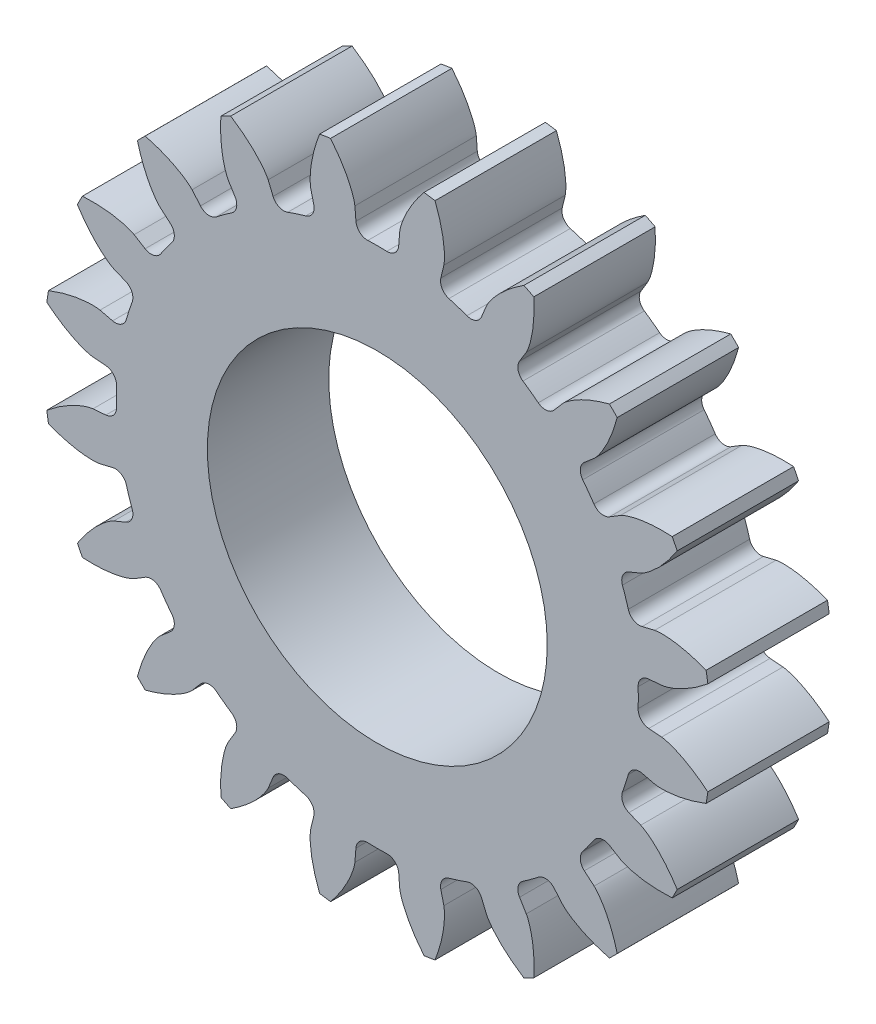
SolidWorks part; units mm, degrees
ref_plane "Front Plane" through (0, 0, 0) normal (0, 0, 1) x (1, 0, 0)
ref_plane "Top Plane" through (0, 0, 0) normal (0, 1, 0) x (1, 0, 0)
ref_plane "Right Plane" through (0, 0, 0) normal (1, 0, 0) x (0, 0, -1)
ref_axis "Gear Axis" through (0, 0, -0.2501) along (0, 0, 1)
sketch "Blank Sketch" plane through (0, 0, 0) normal (0, 0, 1) x (1, 0, 0)
  circle A0 centre (0, 0) radius 13.75
  dimension "OD" = 27.5
extrude "Blank" add sketch "Blank Sketch" along normal blind 5
sketch "Tooth Space Sketch" plane through (0, 0, 0) normal (0, 0, 1) x (1, 0, 0)
  line L0 (11.7099, 0.9227) -> (11.1803, 0.881)
  line L1 (11.7099, -0.9227) -> (11.1803, -0.881)
  line L2 (14.6961, 3.0042) -> (14.6961, -3.0042)
  arc A0 (11.1803, 0.881) -> (10.7429, 0.3902) centre (11.2176, 0.4075) ccw
  arc A1 (10.7429, -0.3902) -> (11.1803, -0.881) centre (11.2176, -0.4075) ccw
  arc A2 (10.7429, -0.3902) -> (10.7429, 0.3902) centre (0, 0) ccw
  spline S0 degree 4 poles (11.7099, 0.9227) (11.7153, 0.9232) (11.7306, 0.925) (11.7593, 0.9294) (11.806, 0.9382) (11.8651, 0.9517) (11.9409, 0.9719) (12.0295, 0.999) (12.1261, 1.0323) (12.2301, 1.0723) (12.3329, 1.1155) (12.4344, 1.1617) (12.5347, 1.2105) (12.6549, 1.2727) (12.7975, 1.3519) (12.9615, 1.4507) (13.1443, 1.5703) (13.3269, 1.7) (13.5034, 1.834) (13.678, 1.9766) (13.8441, 2.1196) (14.0125, 2.2754) (14.1658, 2.4228) (14.3326, 2.5956) (14.4659, 2.7374) (14.6362, 2.9324) (14.7351, 3.0499) (14.8489, 3.1902) (14.8984, 3.2539) (14.9289, 3.293) knots 0 0 0 0 0 0.005377 0.015084 0.028532 0.04661 0.064855 0.092111 0.119476 0.146842 0.174209 0.201575 0.228941 0.256307 0.307035 0.361767 0.4165 0.471232 0.525964 0.580697 0.635429 0.690161 0.744894 0.799626 0.854358 0.909091 0.954545 1 1 1 1 1 construction
  spline S1 degree 4 poles (11.7099, 0.9227) (11.7153, 0.9232) (11.7306, 0.925) (11.7593, 0.9294) (11.806, 0.9382) (11.8651, 0.9517) (11.9409, 0.9719) (12.0295, 0.999) (12.1261, 1.0323) (12.2301, 1.0723) (12.3329, 1.1155) (12.4344, 1.1617) (12.5347, 1.2105) (12.6549, 1.2727) (12.7975, 1.3519) (12.9615, 1.4507) (13.1443, 1.5703) (13.3269, 1.7) (13.5034, 1.834) (13.678, 1.9766) (13.8441, 2.1196) (14.0125, 2.2754) (14.1658, 2.4228) (14.3326, 2.5956) (14.4659, 2.7374) (14.5992, 2.8901) (14.6635, 2.9654) (14.6961, 3.0042) knots 0 0 0 0 0 0.005377 0.015084 0.028532 0.04661 0.064855 0.092111 0.119476 0.146842 0.174209 0.201575 0.228941 0.256307 0.307035 0.361767 0.4165 0.471232 0.525964 0.580697 0.635429 0.690161 0.744894 0.799626 0.854358 0.909091 0.909091 0.909091 0.909091 0.909091
  spline S2 degree 4 poles (11.7099, -0.9227) (11.7153, -0.9232) (11.7306, -0.925) (11.7593, -0.9294) (11.806, -0.9382) (11.8651, -0.9517) (11.9409, -0.9719) (12.0295, -0.999) (12.1261, -1.0323) (12.2301, -1.0723) (12.3329, -1.1155) (12.4344, -1.1617) (12.5347, -1.2105) (12.6549, -1.2727) (12.7975, -1.3519) (12.9615, -1.4507) (13.1443, -1.5703) (13.3269, -1.7) (13.5034, -1.834) (13.678, -1.9766) (13.8441, -2.1196) (14.0125, -2.2754) (14.1658, -2.4228) (14.3326, -2.5956) (14.4659, -2.7374) (14.6362, -2.9324) (14.7351, -3.0499) (14.8489, -3.1902) (14.8984, -3.2539) (14.9289, -3.293) knots 0 0 0 0 0 0.005377 0.015084 0.028532 0.04661 0.064855 0.092111 0.119476 0.146842 0.174209 0.201575 0.228941 0.256307 0.307035 0.361767 0.4165 0.471232 0.525964 0.580697 0.635429 0.690161 0.744894 0.799626 0.854358 0.909091 0.954545 1 1 1 1 1 construction
  spline S3 degree 4 poles (11.7099, -0.9227) (11.7153, -0.9232) (11.7306, -0.925) (11.7593, -0.9294) (11.806, -0.9382) (11.8651, -0.9517) (11.9409, -0.9719) (12.0295, -0.999) (12.1261, -1.0323) (12.2301, -1.0723) (12.3329, -1.1155) (12.4344, -1.1617) (12.5347, -1.2105) (12.6549, -1.2727) (12.7975, -1.3519) (12.9615, -1.4507) (13.1443, -1.5703) (13.3269, -1.7) (13.5034, -1.834) (13.678, -1.9766) (13.8441, -2.1196) (14.0125, -2.2754) (14.1658, -2.4228) (14.3326, -2.5956) (14.4659, -2.7374) (14.5992, -2.8901) (14.6635, -2.9654) (14.6961, -3.0042) knots 0 0 0 0 0 0.005377 0.015084 0.028532 0.04661 0.064855 0.092111 0.119476 0.146842 0.174209 0.201575 0.228941 0.256307 0.307035 0.361767 0.4165 0.471232 0.525964 0.580697 0.635429 0.690161 0.744894 0.799626 0.854358 0.909091 0.909091 0.909091 0.909091 0.909091
  dimension "Root" = 10.75
  dimension "Fillet" = 0.475
extrude "Tooth Space" cut sketch "Tooth Space Sketch" against normal through all both and the other way through all both
pattern_circular "Teeth" count 20 over 360 about axis through (0, 0, -0.2501) along (0, 0, 1) of "Tooth Space"
sketch "Bore Sketch" plane through (0, 0, 0) normal (0, 0, 1) x (1, 0, 0)
  circle A0 centre (0, 0) radius 7
  dimension "Bore" = 14
extrude "Bore" cut sketch "Bore Sketch" against normal through all both and the other way through all both
equation "\"No. of Teeth\"= 20"
equation "\"Module\"= 1.25"
equation "\"Bore Diameter\"= 14"
equation "\"Pressure Angle\"= 20"
equation "\"Outer Diameter\"= ( \"No. of Teeth\" + 2 ) * \"Module\""
equation "\"Pitch Diameter\"= \"No. of Teeth\" * \"Module\""
equation "\"Backlash\"= 0.3 * \"Module\""
equation "\"Arc Length\"= ( ( \"Module\" * pi ) / 2 + \"Backlash\" )"
equation "\"Fillet Radius\"= 0.38 * \"Module\""
equation "\"Tooth Depth\"= IIF ( \"Module\" <= 1.25 , \"Module\" * 2.4 , \"Module\" * 2.25 )"
equation "\"Face Width\"= 5"
equation "\"Root Diameter\"= \"Outer Diameter\" - 2 * \"Tooth Depth\""
equation "\"Base Diameter\"= \"Pitch Diameter\" * cos ( \"Pressure Angle\" )"
equation "\"Base Radius\"= \"Base Diameter\" / 2"
equation "\"Tooth Thickness\"= \"Module\" * pi - \"Arc Length\""
equation "\"Half Space Angle\"= ( \"Arc Length\" / \"Pitch Diameter\" ) * 180 / pi"
equation "\"Involute Fn\"= tan ( \"Pressure Angle\" ) - \"Pressure Angle\" * pi / 180"
equation "\"Flank Offset\"= \"Arc Length\" / \"Pitch Diameter\" - \"Involute Fn\""
equation "\"Tip Cap Diameter\"= \"Outer Diameter\" + 2 * \"Module\""
equation "\"Flank Start Diameter\"= IIF ( \"Base Diameter\" >= ( \"Root Diameter\" + 3 * \"Fillet Radius\" ) , \"Base Diameter\" , \"Root Diameter\" + 3 * \"Fillet Radius\" )"
equation "\"Involute t1\"= ( abs ( ( \"Flank Start Diameter\" / \"Base Diameter\" ) ^ 2 - 1 ) ) ^ 0.5"
equation "\"Involute t2\"= ( abs ( ( \"Tip Cap Diameter\" / \"Base Diameter\" ) ^ 2 - 1 ) ) ^ 0.5"
equation "\"Flank Arc Radius\"= ( \"Pitch Diameter\" / 2 ) * sin ( \"Pressure Angle\" )"
equation "\"Flank Centre Angle\"= \"Half Space Angle\" + \"Pressure Angle\""
equation "\"OD@Blank Sketch\"= \"Outer Diameter\""
equation "\"Width@Blank\"= \"Face Width\""
equation "\"Root@Tooth Space Sketch\"= \"Root Diameter\" / 2"
equation "\"Fillet@Tooth Space Sketch\"= \"Fillet Radius\""
equation "\"Count@Teeth\"= \"No. of Teeth\""
equation "\"Bore@Bore Sketch\"= \"Bore Diameter\""
